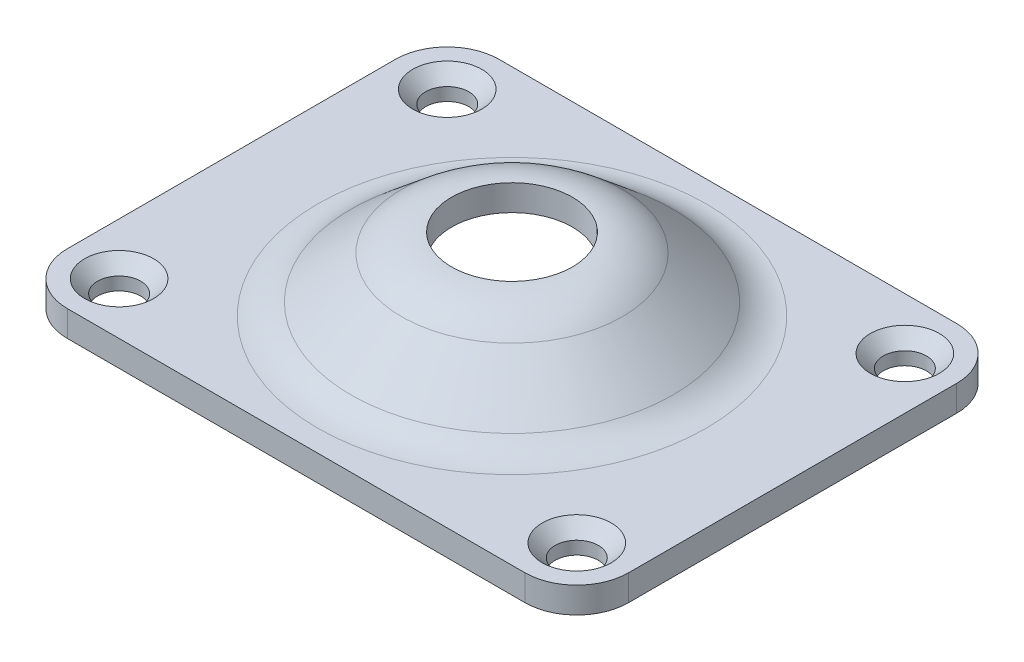
SolidWorks part; units mm, degrees
material "1023 Carbon Steel Sheet (SS)"
ref_plane "Front Plane" through (0, 0, 0) normal (0, 0, 1) x (1, 0, 0)
ref_plane "Top Plane" through (0, 0, 0) normal (0, 1, 0) x (1, 0, 0)
ref_plane "Right Plane" through (0, 0, 0) normal (1, 0, 0) x (0, 0, -1)
sketch "Sketch1" plane through (0, 0, 0) normal (0, 1, 0) x (1, 0, 0)
  line L0 (-1.65, 0) -> (1.65, 0) construction
  line L1 (-26.5, -25) -> (26.5, -25)
  line L2 (-32.5, -19) -> (-32.5, 19)
  line L3 (-26.5, 25) -> (26.5, 25)
  line L4 (32.5, -19) -> (32.5, 19)
  arc A0 (-26.5, -25) -> (-32.5, -19) centre (-26.5, -19) cw
  arc A1 (26.5, -25) -> (32.5, -19) centre (26.5, -19) ccw
  arc A2 (26.5, 25) -> (32.5, 19) centre (26.5, 19) cw
  arc A3 (-32.5, 19) -> (-26.5, 25) centre (-26.5, 19) cw
  circle A4 centre (-26.5, -19) radius 2.5
  circle A5 centre (-26.5, 19) radius 2.5
  circle A6 centre (26.5, 19) radius 2.5
  circle A7 centre (26.5, -19) radius 2.5
  circle A8 centre (0, 0) radius 22.5
  point P0 (0, 0)
  point P8 (-32.5, -25)
  point P11 (32.5, -25)
  point P16 (-32.5, 25)
  dimension "D3" = 6
  dimension "D4" = 5
  dimension "D5" = 5
  dimension "D6" = 5
  dimension "D7" = 5
  dimension "D8" = 45
  dimension "D1" = 50
  dimension "D2" = 65
extrude "Boss-Extrude1" add sketch "Sketch1" along normal blind 3
sketch "Sketch2" plane through (0, 0, 0) normal (0, 0, 1) x (1, 0, 0)
  line L0 (0, 0) -> (0, 11.4249) construction
  line L1 (0, 11.4249) -> (-7, 11.4249) construction
  line L2 (-18.6433, 4.4037) -> (-12.7851, 9.3193)
  line L3 (-26.5, 3) -> (26.5, 3) construction
  line L4 (-16.7149, 2.1056) -> (-10.8567, 7.0212)
  line L5 (-7, 11.4249) -> (-7, 8.4249)
  line L6 (-22.5, 3) -> (-22.5, 0)
  arc A0 (-12.7851, 9.3193) -> (-7, 11.4249) centre (-7, 2.4249) cw
  arc A1 (-18.6433, 4.4037) -> (-22.5, 3) centre (-22.5, 9) cw
  arc A2 (-16.7149, 2.1056) -> (-22.5, 0) centre (-22.5, 9) cw
  arc A3 (-10.8567, 7.0212) -> (-7, 8.4249) centre (-7, 2.4249) cw
  point P4 (0, 5.7125)
  dimension "D1" = 6
  dimension "D2" = 9
  dimension "D3" = 22.5
  dimension "D4" = 7
  dimension "D5" = 50
  dimension "D6" = 3
revolve "Revolve1" add sketch "Sketch2" angle 360 about L0
chamfer "Chamfer1" distance 1.5 angle 45 4 edges at (26.5, 3, 21.5) (-26.5, 3, 21.5) (-26.5, 3, -16.5) (26.5, 3, -16.5)
